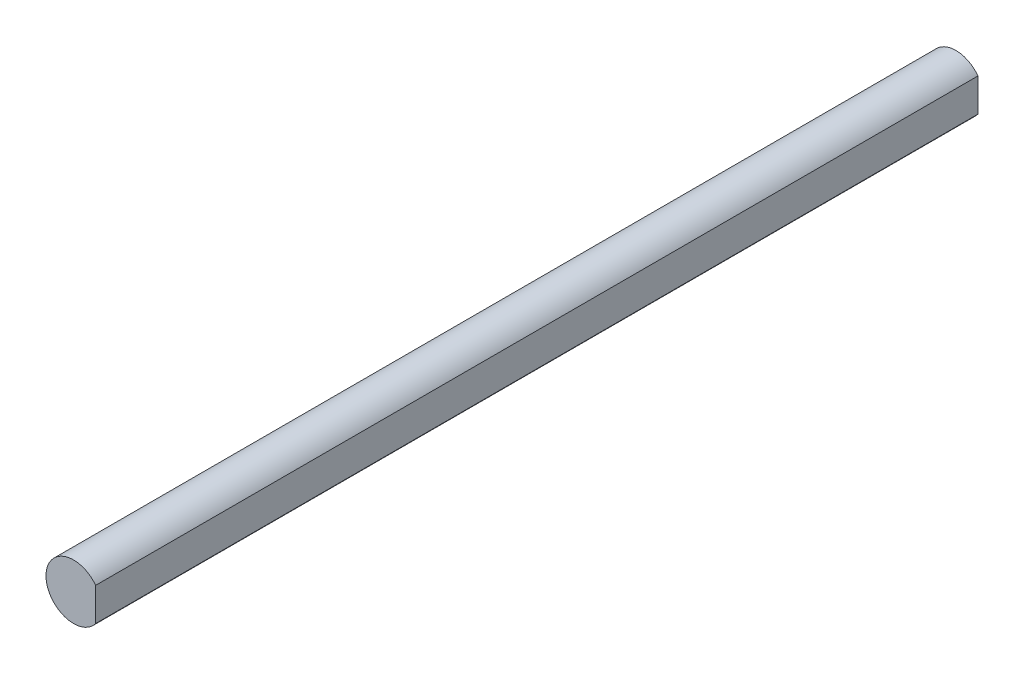
SolidWorks part; units mm, degrees
ref_plane "Plan de face" through (0, 0, 0) normal (0, 0, 1) x (1, 0, 0)
ref_plane "Plan de dessus" through (0, 0, 0) normal (0, 1, 0) x (1, 0, 0)
ref_plane "Plan de droite" through (0, 0, 0) normal (1, 0, 0) x (0, 0, -1)
sketch "Esquisse1" plane through (0, 0, 0) normal (0, 0, 1) x (1, 0, 0)
  circle A0 centre (0, 0) radius 3.175
  dimension "D1" = 6.35
extrude "Boss.-Extru.1" add sketch "Esquisse1" along normal blind 101.6
sketch "Esquisse2" plane through (0, 0, 101.6) normal (0, 0, 1) x (1, 0, 0)
  line L0 (2.54, 1.905) -> (2.54, -1.905)
  line L1 (-3.175, 0) -> (0, 0) construction
  circle A0 centre (0, 0) radius 3.175 construction
  arc A2 (2.54, -1.905) -> (2.54, 1.905) centre (0, 0) ccw
  point P4 (-3.175, 0)
  dimension "D1" = 5.715
extrude "Enlèv. mat.-Extru.1" cut sketch "Esquisse2" against normal through all
